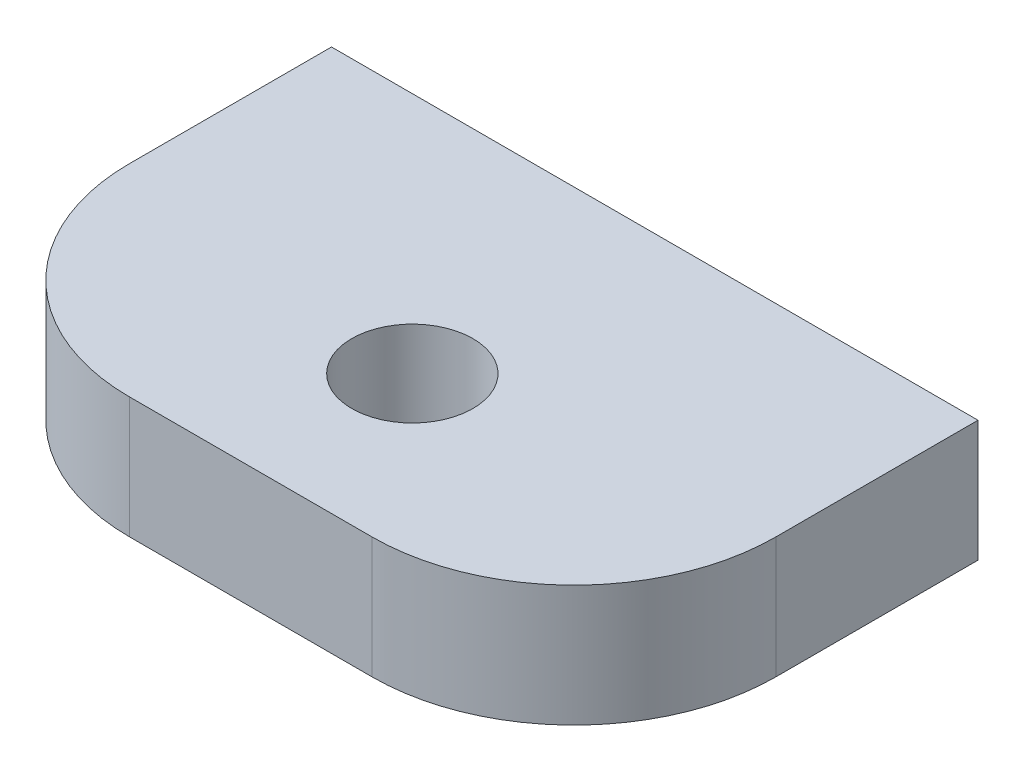
SolidWorks part; units mm, degrees
ref_plane "Front Plane" through (0, 0, 0) normal (0, 0, 1) x (1, 0, 0)
ref_plane "Top Plane" through (0, 0, 0) normal (0, 1, 0) x (1, 0, 0)
ref_plane "Right Plane" through (0, 0, 0) normal (1, 0, 0) x (0, 0, -1)
sketch "Sketch1" plane through (0, 0, 0) normal (0, 1, 0) x (1, 0, 0)
  line L1 (-8, 5) -> (8, 5)
  line L2 (-8, 5) -> (-8, -5)
  line L3 (-8, -5) -> (8, -5)
  line L4 (8, 5) -> (8, -5)
  line L5 (-8, 5) -> (8, -5) construction
  line L6 (-8, -5) -> (8, 5) construction
  point P0 (0, 0)
  point P5 (0, 0)
  dimension "D1" = 16
  dimension "D2" = 10
extrude "Boss-Extrude1" add sketch "Sketch1" along normal blind 3
sketch "Sketch2" plane through (0, 0, 0) normal (0, 1, 0) x (1, 0, 0)
  circle A0 centre (0, -1) radius 1.5
  point P2 (0, -0.9581)
  point P4 (0, -0.8289)
  dimension "D2" = 3
  dimension "D1" = 1
extrude "Cut-Extrude1" cut sketch "Sketch2" along normal up to next
fillet "Fillet1" radius 5 2 edges at (8, 1.5, 5) (-8, 1.5, 5)
